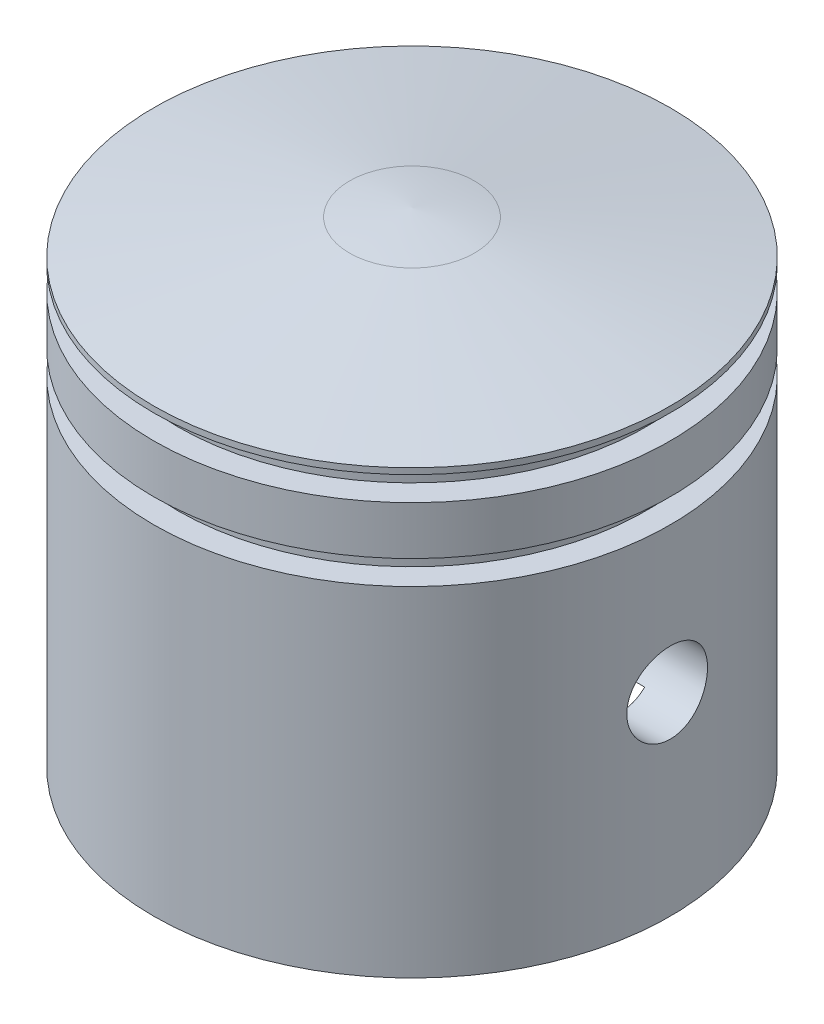
SolidWorks part; units mm, degrees
ref_plane "Front Plane" through (0, 0, 0) normal (0, 0, 1) x (1, 0, 0)
ref_plane "Top Plane" through (0, 0, 0) normal (0, 1, 0) x (1, 0, 0)
ref_plane "Right Plane" through (0, 0, 0) normal (1, 0, 0) x (0, 0, -1)
sketch "Sketch1" plane through (0, 0, 0) normal (0, 0, 1) x (1, 0, 0)
  line L0 (0, 0) -> (16, 0)
  line L1 (16, 0) -> (16, 27.3722)
  line L2 (16, 27.3722) -> (3.8725, 29.5106)
  line L3 (0, 30) -> (0, 0)
  line L4 (0, 30) -> (23.7398, 30) construction
  arc A0 (3.8725, 29.5106) -> (0, 30) centre (-3.0734, -9.8817) ccw
  dimension "D4" = 40
  dimension "D1" = 30
  dimension "D2" = 16
  dimension "D3" = 10
revolve "Revolve1" add sketch "Sketch1" angle 360 about L3
sketch "Sketch2" plane through (0, 0, 0) normal (0, 0, 1) x (1, 0, 0)
  line L0 (0, 0) -> (0, 31.0027) construction
  line L1 (-16, 0) -> (16, 0) construction
  line L2 (14.5, 27) -> (17.7807, 27)
  line L3 (14.5, 27) -> (14.5, 25.5)
  line L4 (14.5, 25.5) -> (17.7807, 25.5)
  line L5 (17.7807, 27) -> (17.7807, 25.5)
  line L6 (14.5, 22.5) -> (17.7807, 22.5)
  line L7 (14.5, 22.5) -> (14.5, 21)
  line L8 (14.5, 21) -> (17.7807, 21)
  line L9 (17.7807, 22.5) -> (17.7807, 21)
  dimension "D1" = 3
  dimension "D2" = 1.5
  dimension "D3" = 1.5
  dimension "D4" = 21
  dimension "D5" = 14.5
revolve "Cut-Revolve1" cut sketch "Sketch2" angle 360 about L0
sketch "Sketch3" plane through (0, 0, 0) normal (0, -1, 0) x (1, 0, 0)
  circle A0 centre (0, 0) radius 10
  dimension "D1" = 20
extrude "Cut-Extrude1" cut sketch "Sketch3" against normal blind 24
sketch "Sketch4" plane through (0, 0, 0) normal (0, -1, 0) x (1, 0, 0)
  circle A0 centre (0, 0) radius 13
  dimension "D1" = 26
extrude "Cut-Extrude2" cut sketch "Sketch4" against normal blind 10
sketch "Sketch5" plane through (0, 0, 0) normal (1, 0, 0) x (0, 0, -1)
  line L0 (-16, 0) -> (16, 0) construction
  circle A0 centre (0, 12) radius 2.5
  dimension "D1" = 5
  dimension "D2" = 12
extrude "Cut-Extrude4" cut sketch "Sketch5" against normal through all both and the other way through all contours A0
